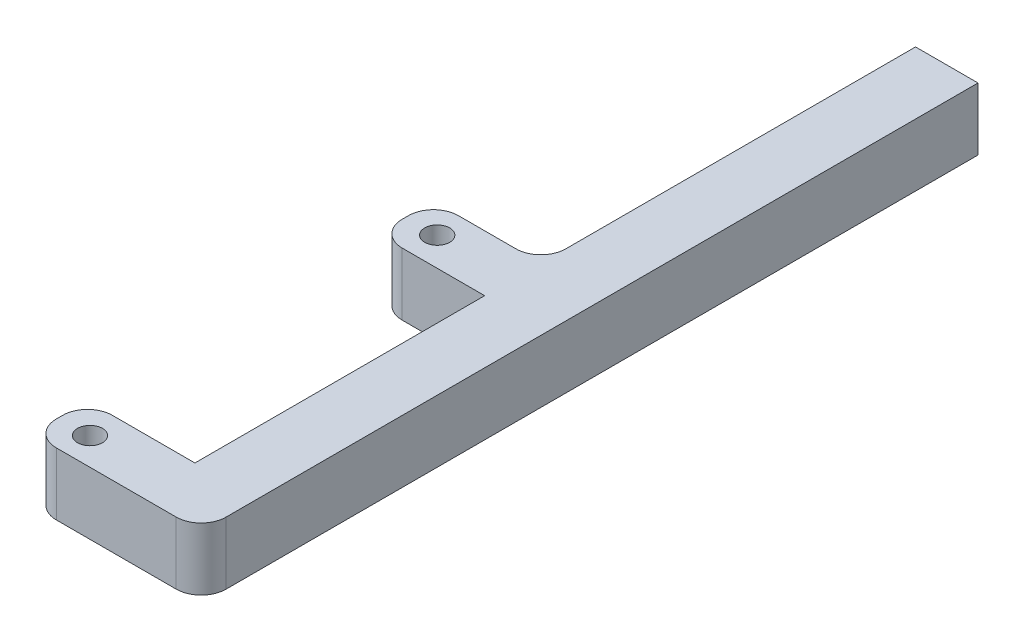
SolidWorks part; units mm, degrees
ref_plane "Front Plane" through (0, 0, 0) normal (0, 0, 1) x (1, 0, 0)
ref_plane "Top Plane" through (0, 0, 0) normal (0, 1, 0) x (1, 0, 0)
ref_plane "Right Plane" through (0, 0, 0) normal (1, 0, 0) x (0, 0, -1)
sketch "Sketch1" plane through (0, 0, 0) normal (0, 1, 0) x (1, 0, 0)
  line L0 (0, 4.5) -> (8.6, 4.5)
  line L1 (0, 0) -> (13.6, 0)
  line L2 (0, 0) -> (0, 4.5)
  line L3 (8.6, 62.2) -> (13.6, 62.2)
  line L4 (13.6, 0) -> (13.6, 62.2)
  line L5 (8.6, 4.5) -> (8.6, 27.7)
  line L6 (0, 27.7) -> (8.6, 27.7)
  line L7 (0, 27.7) -> (0, 32.2)
  line L8 (0, 32.2) -> (8.6, 32.2)
  line L9 (8.6, 32.2) -> (8.6, 62.2)
  circle A0 centre (2.5, 2.2) radius 1
  circle A1 centre (2.5, 30) radius 1
  dimension "D1" = 2
  dimension "D2" = 2
  dimension "D8" = 27.8
  dimension "D3" = 4.5
  dimension "D4" = 6.1
  dimension "D5" = 2.5
  dimension "D6" = 5
  dimension "D7" = 4.5
  dimension "D9" = 2.3
  dimension "D10" = 2.3
  dimension "D11" = 2.5
  dimension "D12" = 30
extrude "Boss-Extrude1" add sketch "Sketch1" along normal blind 5
fillet "Fillet1" radius 2 6 edges at (0, 2.5, -4.5) (13.6, 2.5, 0) (8.6, 2.5, -32.2) (0, 2.5, 0) (0, 2.5, -32.2) (0, 2.5, -27.7)
